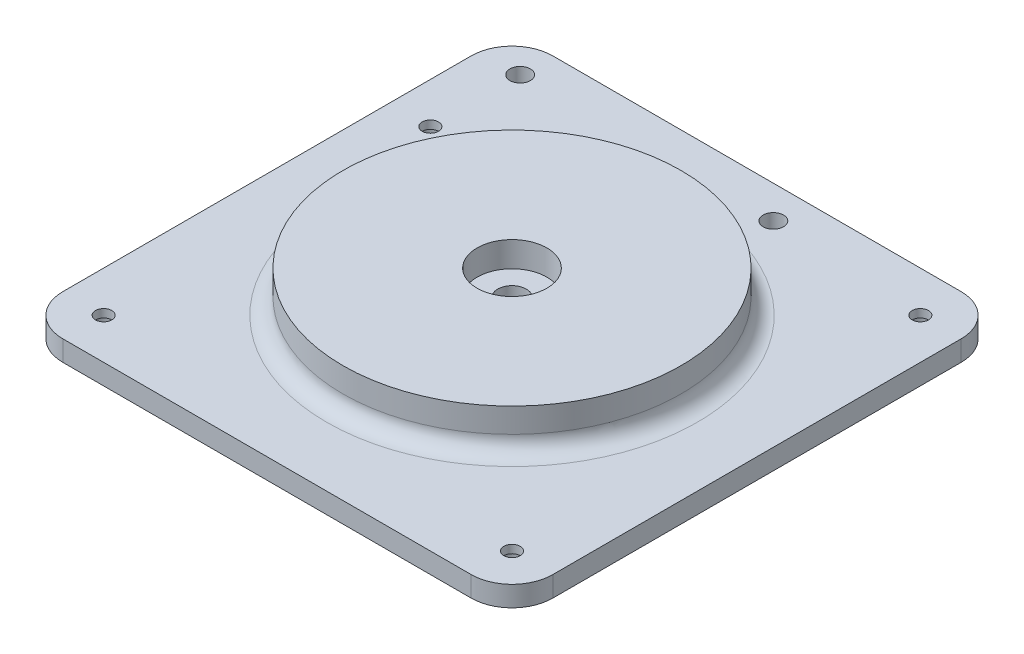
SolidWorks part; units mm, degrees
ref_plane "Alzado" through (0, 0, 0) normal (0, 0, 1) x (1, 0, 0)
ref_plane "Planta" through (0, 0, 0) normal (0, 1, 0) x (1, 0, 0)
ref_plane "Vista lateral" through (0, 0, 0) normal (1, 0, 0) x (0, 0, -1)
sketch "Croquis1" plane through (0, 0, 0) normal (0, 1, 0) x (1, 0, 0)
  circle A0 centre (0, 0) radius 41.4
  dimension "D1" = 82.8
extrude "Saliente-Extruir1" add sketch "Croquis1" along normal blind 10
sketch "Croquis3" plane through (0, 0, 0) normal (0, -1, 0) x (1, 0, 0)
  line L1 (-60, 60) -> (60, 60)
  line L2 (-60, 60) -> (-60, -60)
  line L3 (-60, -60) -> (60, -60)
  line L4 (60, 60) -> (60, -60)
  line L5 (-60, 60) -> (60, -60) construction
  line L6 (-60, -60) -> (60, 60) construction
  point P0 (0, 0)
  dimension "D1" = 120
  dimension "D2" = 120
extrude "Saliente-Extruir2" add sketch "Croquis3" along normal blind 5
sketch "Croquis2" plane through (0, 10, 0) normal (0, 1, 0) x (1, 0, 0)
  circle A0 centre (0, 0) radius 3.5
  dimension "D1" = 7
extrude "Cortar-Extruir1" cut sketch "Croquis2" against normal through all
sketch "Croquis4" plane through (0, -5, 0) normal (0, -1, 0) x (1, 0, 0)
  circle A0 centre (0, 0) radius 8.5
  dimension "D1" = 17
extrude "Cortar-Extruir2" cut sketch "Croquis4" against normal blind 6
ref_plane "Plano1" through (0, 0, -43) normal (0, 0, 1) x (1, 0, 0)
sketch "Croquis5" plane through (0, 0, -43) normal (0, 0, 1) x (1, 0, 0)
  line L0 (-60, -5) -> (60, -5) construction
  line L1 (-40.65, -5) -> (1.65, -5)
  line L2 (-40.65, -5) -> (-40.65, -47.3)
  line L3 (-40.65, -47.3) -> (1.65, -47.3)
  line L4 (1.65, -5) -> (1.65, -47.3)
  point P6 (-19.5, -5)
  dimension "D1" = 42.3
  dimension "D2" = 42.3
  dimension "D3" = 19.5
extrude "Saliente-Extruir3" add sketch "Croquis5" against normal blind 5
fillet "Redondeo1" radius 4 1 edges at (0, 0, 41.4)
sketch "Croquis8" plane through (0, 0, -48) normal (0, 0, -1) x (-1, 0, 0)
  line L2 (40.65, -47.3) -> (-1.65, -47.3) construction
  line L3 (-1.65, -47.3) -> (-1.65, -5) construction
  line L4 (40.65, -5) -> (40.65, -47.3) construction
  line L6 (40.65, -47.3) -> (-1.65, -47.3) construction
  circle A0 centre (4, -10.65) radius 2
  circle A1 centre (35, -10.65) radius 2
  circle A2 centre (35, -41.65) radius 2
  circle A3 centre (4, -41.65) radius 2
  circle A4 centre (19.5, -26.15) radius 11.5
  point P17 (19.5, -47.3)
  dimension "D3" = 4
  dimension "D4" = 4
  dimension "D5" = 4
  dimension "D6" = 4
  dimension "D9" = 23
  dimension "D1" = 31
  dimension "D2" = 31
  dimension "D7" = 5.65
  dimension "D8" = 5.65
  dimension "D10" = 21.15
  dimension "D11" = 21.15
extrude "Cortar-Extruir3" cut sketch "Croquis8" against normal up to next
sketch "Croquis9" plane through (0, -5, 0) normal (0, -1, 0) x (1, 0, 0)
  line L0 (60, 60) -> (-60, 60) construction
  line L1 (-60, -60) -> (60, -60) construction
  line L2 (-60, 60) -> (-60, -60) construction
  line L3 (60, -60) -> (60, 60) construction
  circle A0 centre (-50, 50) radius 3
  circle A1 centre (50, 50) radius 3
  circle A2 centre (50, -50) radius 3
  circle A3 centre (-50, -30) radius 3
  dimension "D1" = 6
  dimension "D2" = 6
  dimension "D3" = 6
  dimension "D4" = 6
  dimension "D5" = 10
  dimension "D6" = 30
  dimension "D7" = 10
  dimension "D8" = 10
  dimension "D9" = 10
extrude "Cortar-Extruir4" cut sketch "Croquis9" against normal blind 3
sketch "Croquis10" plane through (0, -2, 0) normal (0, -1, 0) x (1, 0, 0)
  circle A0 centre (-50, 50) radius 2
  circle A1 centre (50, 50) radius 2
  circle A2 centre (50, -50) radius 2
  circle A3 centre (-50, -30) radius 2
  dimension "D1" = 4
  dimension "D2" = 4
  dimension "D3" = 4
  dimension "D4" = 4
extrude "Cortar-Extruir5" cut sketch "Croquis10" against normal up to next
sketch "Croquis11" plane through (1.65, 0, 0) normal (1, 0, 0) x (0, 0, -1)
  line L1 (43, -47.3) -> (60, -47.3)
  line L2 (43, -47.3) -> (43, -5)
  line L3 (43, -5) -> (60, -5)
  line L4 (60, -47.3) -> (60, -5)
extrude "Saliente-Extruir4" add sketch "Croquis11" along normal blind 3
sketch "Croquis12" plane through (-40.65, 0, 0) normal (-1, 0, 0) x (0, 0, 1)
  line L1 (-43, -47.3) -> (-60, -47.3)
  line L2 (-43, -47.3) -> (-43, -5)
  line L3 (-43, -5) -> (-60, -5)
  line L4 (-60, -47.3) -> (-60, -5)
extrude "Saliente-Extruir5" add sketch "Croquis12" along normal blind 3
sketch "Croquis15" plane through (-43.65, 0, 0) normal (-1, 0, 0) x (0, 0, 1)
  line L0 (-43, -47.3) -> (-43, -5) construction
  line L1 (-43, -5) -> (-60, -5)
  line L2 (-43, -5) -> (-43, -8)
  line L3 (-43, -8) -> (-60, -8)
  line L4 (-60, -5) -> (-60, -8)
  line L7 (-60, -5) -> (-60, -47.3) construction
  dimension "D1" = 3
extrude "Saliente-Extruir6" add sketch "Croquis15" along normal blind 14
sketch "Croquis16" plane through (4.65, 0, 0) normal (1, 0, 0) x (0, 0, -1)
  line L0 (60, -47.3) -> (60, -5) construction
  line L1 (43, -5) -> (60, -5)
  line L2 (43, -5) -> (43, -8)
  line L3 (43, -8) -> (60, -8)
  line L4 (60, -5) -> (60, -8)
  dimension "D1" = 3
extrude "Saliente-Extruir7" add sketch "Croquis16" along normal blind 15
sketch "Croquis13" plane through (0, 0, 0) normal (0, 1, 0) x (1, 0, 0)
  line L0 (-60, 60) -> (60, 60) construction
  line L2 (-60, -60) -> (-60, 60) construction
  circle A0 centre (-50, 52) radius 2.5
  circle A1 centre (12, 52) radius 2.5
  dimension "D1" = 5
  dimension "D2" = 5
  dimension "D3" = 8
  dimension "D5" = 62
  dimension "D6" = 10
extrude "Cortar-Extruir6" cut sketch "Croquis13" against normal blind 10
sketch "Croquis17" plane through (0, 0, -60) normal (0, 0, -1) x (-1, 0, 0)
  line L5 (-60, -5) -> (79.5455, -5)
  line L6 (-60, -5) -> (-60, -48.7976)
  line L7 (-60, -48.7976) -> (79.5455, -48.7976)
  line L8 (79.5455, -5) -> (79.5455, -48.7976)
extrude "Cortar-Extruir7" cut sketch "Croquis17" against normal up to surface (120 mm away) up to face at (0, -2.5, 60)
fillet "Redondeo2" radius 10 1 edges at (60, -2.5, -60)
fillet "Redondeo3" radius 10 1 edges at (-60, -2.5, -60)
fillet "Redondeo4" radius 10 1 edges at (-60, -2.5, 60)
fillet "Redondeo5" radius 10 1 edges at (60, -2.5, 60)
sketch "Croquis18" plane through (0, 10, 0) normal (0, 1, 0) x (1, 0, 0)
  circle A0 centre (0, 0) radius 8.55
  dimension "D1" = 17.1
extrude "Cortar-Extruir8" cut sketch "Croquis18" against normal blind 6.2
